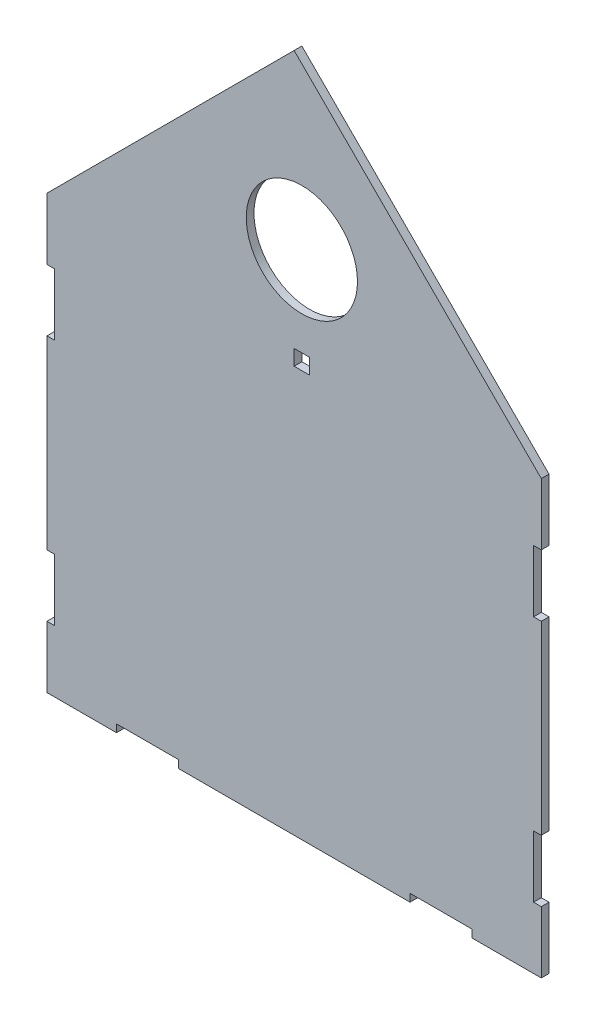
SolidWorks part; units mm, degrees
ref_plane "Front Plane" through (0, 0, 0) normal (0, 0, 1) x (1, 0, 0)
ref_plane "Top Plane" through (0, 0, 0) normal (0, 1, 0) x (1, 0, 0)
ref_plane "Right Plane" through (0, 0, 0) normal (1, 0, 0) x (0, 0, -1)
sketch "Sketch2" plane through (0, 0, 0) normal (0, 0, 1) x (1, 0, 0)
  line L0 (0.5643, 279.4) -> (-101.0357, 177.8)
  line L1 (-101.0357, 177.8) -> (102.1643, 177.8) construction
  line L2 (102.1643, 177.8) -> (0.5643, 279.4)
  line L3 (-101.0357, 177.8) -> (-101.0357, 152.4)
  line L4 (-101.0357, 152.4) -> (-97.8607, 152.4)
  line L5 (-97.8607, 152.4) -> (-97.8607, 127)
  line L6 (-97.8607, 127) -> (-101.0357, 127)
  line L7 (-101.0357, 127) -> (-101.0357, 50.8)
  line L8 (-101.0357, 50.8) -> (-97.8607, 50.8)
  line L9 (-97.8607, 50.8) -> (-97.8607, 25.4)
  line L10 (-97.8607, 25.4) -> (-101.0357, 25.4)
  line L11 (-101.0357, 25.4) -> (-101.0357, 0)
  line L12 (-101.0357, 0) -> (-72.4607, 0)
  line L13 (102.1643, 0) -> (102.1643, 25.4)
  line L14 (102.1643, 25.4) -> (98.9893, 25.4)
  line L15 (98.9893, 25.4) -> (98.9893, 50.8)
  line L16 (98.9893, 50.8) -> (102.1643, 50.8)
  line L17 (102.1643, 50.8) -> (102.1643, 127)
  line L18 (102.1643, 127) -> (98.9893, 127)
  line L19 (98.9893, 127) -> (98.9893, 152.4)
  line L20 (98.9893, 152.4) -> (102.1643, 152.4)
  line L21 (102.1643, 152.4) -> (102.1643, 177.8)
  line L22 (-72.4607, 0) -> (-72.4607, 3.175)
  line L23 (-72.4607, 3.175) -> (-47.0607, 3.175)
  line L24 (-47.0607, 3.175) -> (-47.0607, 0)
  line L25 (-47.0607, 0) -> (48.1893, 0)
  line L26 (48.1893, 0) -> (48.1893, 3.175)
  line L27 (48.1893, 3.175) -> (73.5893, 3.175)
  line L28 (73.5893, 3.175) -> (73.5893, 0)
  line L29 (73.5893, 0) -> (102.1643, 0)
  dimension "D1" = 203.2
  dimension "D2" = 101.6
  dimension "D3" = 25.4
  dimension "D4" = 3.175
  dimension "D5" = 25.4
  dimension "D6" = 25.4
  dimension "D7" = 3.175
  dimension "D8" = 25.4
  dimension "D9" = 95.25
  dimension "D10" = 3.175
  dimension "D11" = 3.175
  dimension "D14" = 3.175
  dimension "D15" = 76.2
extrude "Boss-Extrude1" add sketch "Sketch2" along normal blind 3.175
sketch "Sketch3" plane through (0, 0, 3.175) normal (0, 0, 1) x (1, 0, 0)
  circle A1 centre (3.7393, 210.0783) radius 22.86
  dimension "D2" = 45.72
extrude "Cut-Extrude1" cut sketch "Sketch3" against normal blind 3.175
sketch "Sketch5" plane through (0, 0, 3.175) normal (0, 0, 1) x (1, 0, 0)
  line L2 (0.5643, 173.3348) -> (6.9143, 173.3348)
  line L3 (0.5643, 173.3348) -> (0.5643, 166.9848)
  line L4 (0.5643, 166.9848) -> (6.9143, 166.9848)
  line L5 (6.9143, 173.3348) -> (6.9143, 166.9848)
  dimension "D1" = 6.35
extrude "Cut-Extrude2" cut sketch "Sketch5" against normal blind 3.175
